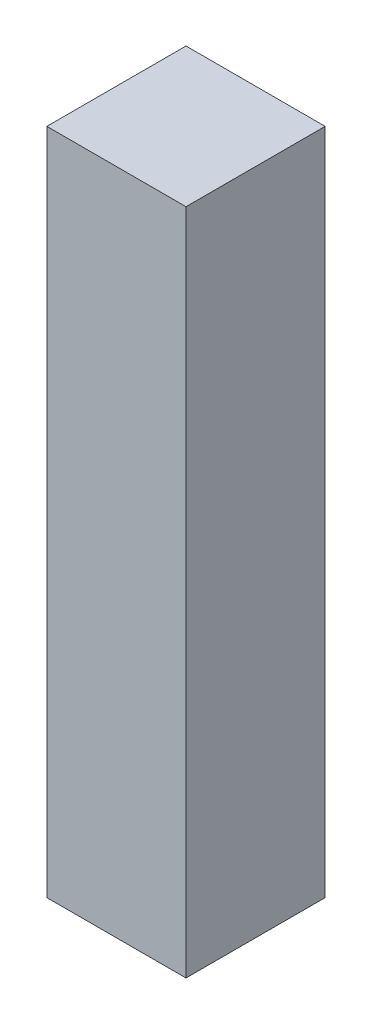
SolidWorks part; units mm, degrees
ref_plane "Front Plane" through (0, 0, 0) normal (0, 0, 1) x (1, 0, 0)
ref_plane "Top Plane" through (0, 0, 0) normal (0, 1, 0) x (1, 0, 0)
ref_plane "Right Plane" through (0, 0, 0) normal (1, 0, 0) x (0, 0, -1)
other "Configuration Table"
sketch "Sketch1" plane through (0, 0, 0) normal (0, 0, 1) x (1, 0, 0)
  line L1 (330, 508) -> (370, 508)
  line L2 (330, 508) -> (330, 700)
  line L3 (330, 700) -> (370, 700)
  line L4 (370, 508) -> (370, 700)
extrude "PACK_kapak_postu_dikey_1" add sketch "Sketch1" against normal blind 40 from offset 380 separate body
